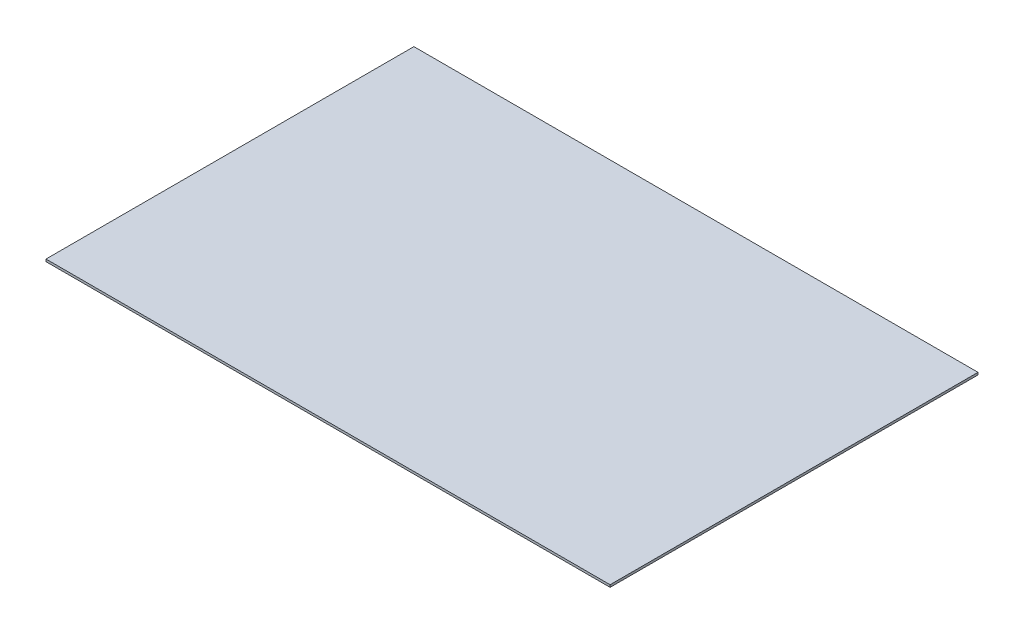
SolidWorks part; units mm, degrees
ref_plane "Front Plane" through (0, 0, 0) normal (0, 0, 1) x (1, 0, 0)
ref_plane "Top Plane" through (0, 0, 0) normal (0, 1, 0) x (1, 0, 0)
ref_plane "Right Plane" through (0, 0, 0) normal (1, 0, 0) x (0, 0, -1)
sketch "Sketch1" plane through (0, 0, 0) normal (0, 1, 0) x (1, 0, 0)
  line L1 (-584.2, 381) -> (584.2, 381)
  line L2 (-584.2, 381) -> (-584.2, -381)
  line L3 (-584.2, -381) -> (584.2, -381)
  line L4 (584.2, 381) -> (584.2, -381)
  line L5 (-584.2, 381) -> (584.2, -381) construction
  line L6 (-584.2, -381) -> (584.2, 381) construction
  point P0 (0, 0)
  dimension "D1" = 762
  dimension "D2" = 1168.4
extrude "Boss-Extrude1" add sketch "Sketch1" along normal blind 4.7625
